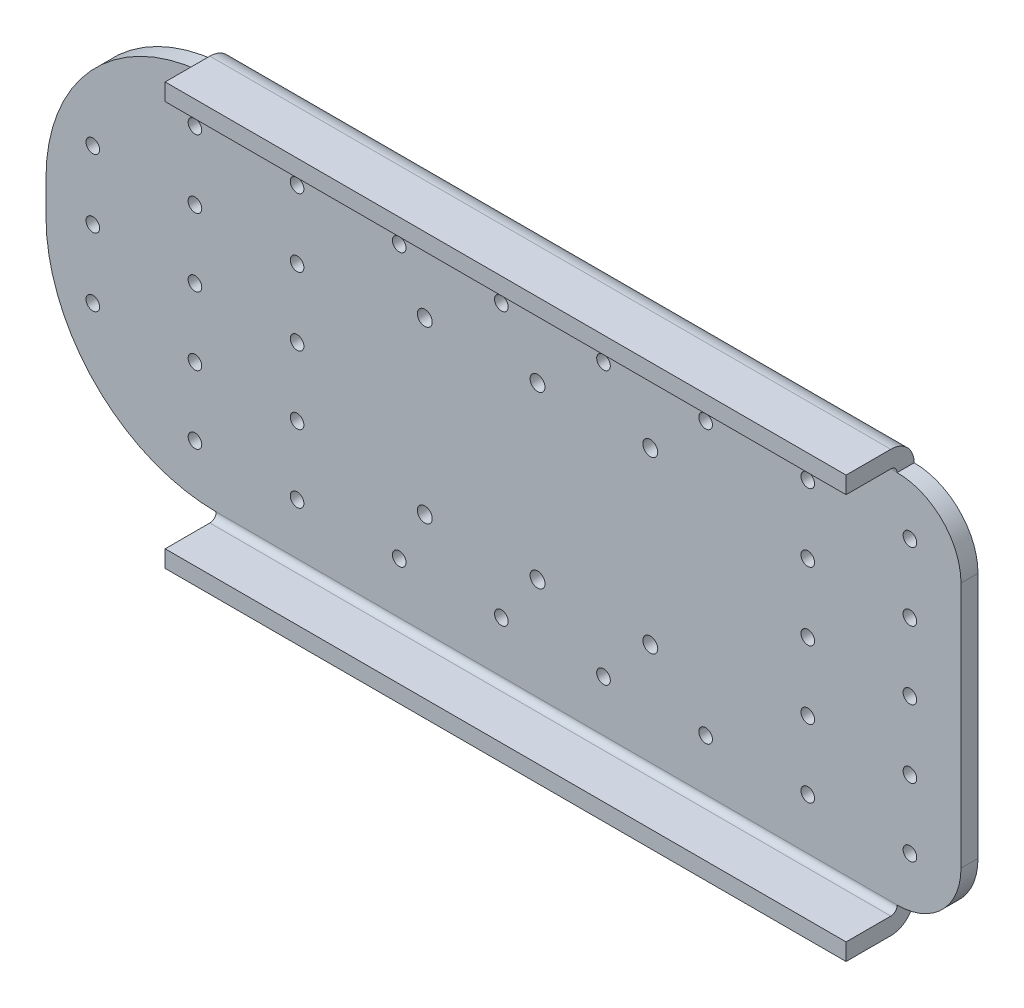
SolidWorks part; units mm, degrees
ref_plane "Front Plane" through (0, 0, 0) normal (0, 0, 1) x (1, 0, 0)
ref_plane "Top Plane" through (0, 0, 0) normal (0, 1, 0) x (1, 0, 0)
ref_plane "Right Plane" through (0, 0, 0) normal (1, 0, 0) x (0, 0, -1)
sketch "Sketch1" plane through (0, 0, 0) normal (0, 0, 1) x (1, 0, 0)
  line L1 (-26.5, 20) -> (26.5, 20) construction
  line L2 (-26.5, 20) -> (-26.5, -20) construction
  line L3 (-26.5, -20) -> (26.5, -20) construction
  line L4 (26.5, 20) -> (26.5, -20) construction
  line L5 (0, -20) -> (0, 20) construction
  line L6 (-26.5, 0) -> (26.5, 0) construction
  line L7 (-115.5, 44) -> (99.5, 44)
  line L8 (-115.5, 44) -> (-115.5, -44)
  line L9 (-115.5, -44) -> (99.5, -44)
  line L10 (99.5, 44) -> (99.5, -44)
  line L11 (-8, -44) -> (-8, 44) construction
  line L12 (-115.5, 0) -> (99.5, 0) construction
  circle A0 centre (-26.5, 20) radius 1.75
  circle A1 centre (26.5, 20) radius 1.75
  circle A2 centre (-26.5, -20) radius 1.75
  circle A3 centre (26.5, -20) radius 1.75
  circle A4 centre (0, 20) radius 1.75
  circle A5 centre (0, -20) radius 1.75
  point P0 (0, 0)
  point P10 (-8, 0)
  dimension "D3" = 3.5
  dimension "D1" = 53
  dimension "D2" = 40
  dimension "D4" = 215
  dimension "D5" = 88
  dimension "D6" = 73
extrude "Boss-Extrude1" add sketch "Sketch1" along normal blind 4
fillet "Fillet1" radius 15 2 edges at (99.5, -44, 2) (99.5, 44, 2)
fillet "Fillet2" radius 40 2 edges at (-115.5, -44, 2) (-115.5, 44, 2)
ref_plane "Plane1" through (-75.5, 0, 0) normal (-1, 0, 0) x (0, 0, 1)
sketch "Sketch2" plane through (-75.5, 0, 0) normal (-1, 0, 0) x (0, 0, 1)
  line L0 (0, -44) -> (4, -44)
  line L1 (4, -44) -> (0, -44) construction
  line L2 (5.5, -45.5) -> (16, -45.5)
  line L3 (16, -45.5) -> (16, -49.5)
  line L4 (16, -49.5) -> (5.5, -49.5)
  line L5 (0, -4) -> (0, -44) construction
  line L6 (4, -44) -> (4, -4) construction
  line L7 (0, 0) -> (-14.579, 0) construction
  line L8 (16, 49.5) -> (5.5, 49.5)
  line L9 (16, 45.5) -> (16, 49.5)
  line L10 (5.5, 45.5) -> (16, 45.5)
  line L11 (0, 44) -> (4, 44)
  arc A0 (4, -44) -> (5.5, -45.5) centre (5.5, -44) ccw
  arc A1 (5.5, -49.5) -> (0, -44) centre (5.5, -44) cw
  arc A2 (5.5, 49.5) -> (0, 44) centre (5.5, 44) ccw
  arc A3 (4, 44) -> (5.5, 45.5) centre (5.5, 44) cw
  dimension "D1" = 1.5
  dimension "D2" = 12
extrude "Boss-Extrude2" add sketch "Sketch2" against normal up to vertex (160 mm away)
sketch "Sketch3" plane through (0, 0, 4) normal (0, 0, 1) x (1, 0, 0)
  line L0 (-105.5, 0) -> (87.5, 0) construction
  line L1 (-102.5, -16) -> (87.5, -16) construction
  line L2 (-85.5, -32) -> (87.5, -32) construction
  line L4 (99.5, -29) -> (99.5, 29) construction
  line L9 (-33.5, 25.5) -> (48.5, 25.5) construction
  line L10 (-33.5, 25.5) -> (-33.5, -25.5) construction
  line L11 (-33.5, -25.5) -> (48.5, -25.5) construction
  line L12 (48.5, 25.5) -> (48.5, -25.5) construction
  line L13 (7.5, -25.5) -> (7.5, 25.5) construction
  line L14 (-33.5, 0) -> (48.5, 0) construction
  circle A0 centre (63.5, -32) radius 1.6
  circle A1 centre (39.5, -32) radius 1.6
  circle A2 centre (26.5, 20) radius 1.75 construction
  circle A5 centre (15.5, -32) radius 1.6
  circle A11 centre (87.5, -32) radius 1.6
  circle A16 centre (87.5, -16) radius 1.6
  circle A17 centre (-8.5, -32) radius 1.6
  circle A18 centre (-32.5, -32) radius 1.6
  circle A19 centre (-56.5, -32) radius 1.6
  circle A20 centre (-80.5, -32) radius 1.6
  circle A21 centre (87.5, 0) radius 1.6
  circle A22 centre (63.5, -16) radius 1.6
  circle A23 centre (63.5, 0) radius 1.6
  circle A25 centre (-56.5, -16) radius 1.6
  circle A26 centre (-80.5, -16) radius 1.6
  circle A27 centre (-104.5, -16) radius 1.6
  circle A28 centre (-56.5, 0) radius 1.6
  circle A29 centre (-80.5, 0) radius 1.6
  circle A30 centre (-104.5, 0) radius 1.6
  point P7 (7.5, 0)
  dimension "D8" = 3.2
  dimension "D1" = 16
  dimension "D2" = 16
  dimension "D3" = 12
  dimension "D5" = 82
  dimension "D6" = 51
  dimension "D7" = 22
  dimension "D4" = 173
  dimension "D9" = 190
  dimension "D10" = 193
  dimension "D12" = 24
  dimension "D14" = 24
  dimension "D18" = 24
  dimension "D11" = 8
  dimension "D15" = 2
  dimension "D16" = 2
  dimension "D13" = 3
  dimension "D17" = 3
extrude "Cut-Extrude1" cut sketch "Sketch3" against normal blind 4
mirror "Mirror5" about plane through (0, 0, 0) normal (0, 1, 0) of "Cut-Extrude1"
surface "Surface-Offset1" parameters "D1"=0
equation "\"D14@Sketch3\"=\"D12@Sketch3\""
equation "\"D18@Sketch3\"=\"D14@Sketch3\""
